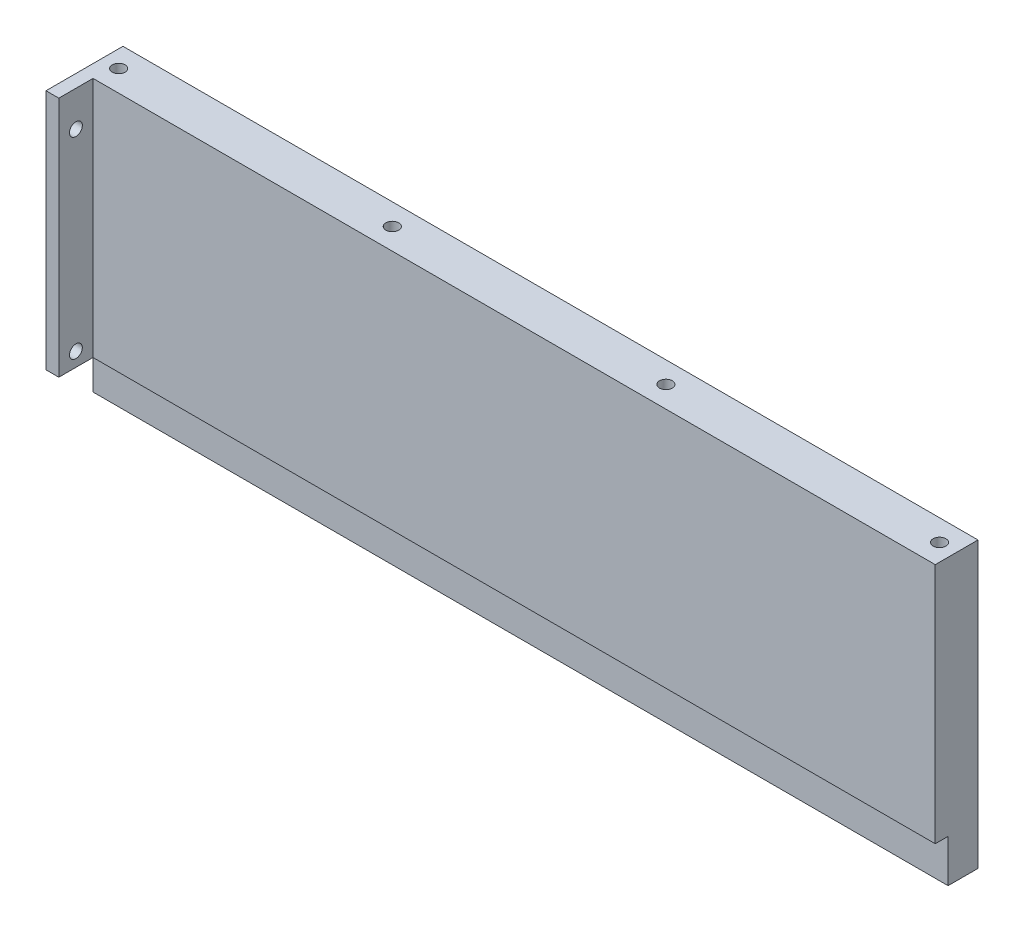
SolidWorks part; units mm, degrees
ref_plane "Front Plane" through (0, 0, 0) normal (0, 0, 1) x (1, 0, 0)
ref_plane "Top Plane" through (0, 0, 0) normal (0, 1, 0) x (1, 0, 0)
ref_plane "Right Plane" through (0, 0, 0) normal (1, 0, 0) x (0, 0, -1)
sketch "Sketch1" plane through (0, 0, 0) normal (0, 1, 0) x (1, 0, 0)
  line L1 (-100, -5) -> (100, -5)
  line L2 (-100, -5) -> (-100, 5)
  line L3 (-100, 5) -> (100, 5)
  line L4 (100, -5) -> (100, 5)
  line L5 (-100, -5) -> (100, 5) construction
  line L6 (-100, 5) -> (100, -5) construction
  point P0 (0, 0)
  point P8 (0, 0)
  dimension "D1" = 200
  dimension "D2" = 10
extrude "Boss-Extrude1" add sketch "Sketch1" along normal blind 66.54
sketch "Sketch2" plane through (0, 66.54, 0) normal (0, 1, 0) x (1, 0, 0)
  line L0 (-100, 5) -> (-100, -5) construction
  line L1 (-100, -5) -> (100, -5) construction
  circle A0 centre (-96, 0) radius 1.5
  point P4 (0, 0)
  dimension "D1" = 3
  dimension "D2" = 4
  dimension "D3" = 5
extrude "Cut-Extrude1" cut sketch "Sketch2" against normal up to next
pattern_linear "LPattern1" count 4 spacing 64 along (1, 0, 0) of "Cut-Extrude1"
sketch "Sketch3" plane through (0, 0, 5) normal (0, 0, 1) x (1, 0, 0)
  line L0 (100, 66.54) -> (100, 0) construction
  line L1 (-100, 0) -> (100, 0)
  line L2 (-100, 0) -> (-100, 10)
  line L3 (-100, 10) -> (100, 10)
  line L4 (100, 0) -> (100, 10)
  dimension "D1" = 10
extrude "Cut-Extrude2" cut sketch "Sketch3" against normal blind 3
sketch "Sketch4" plane through (0, 0, 5) normal (0, 0, 1) x (1, 0, 0)
  line L0 (100, 10) -> (-100, 10) construction
  line L1 (-100, 66.54) -> (-97, 66.54)
  line L2 (-100, 66.54) -> (-100, 10)
  line L3 (-100, 10) -> (-97, 10)
  line L4 (-97, 66.54) -> (-97, 10)
  dimension "D1" = 3
extrude "Boss-Extrude2" add sketch "Sketch4" along normal blind 8
sketch "Sketch5" plane through (-100, 0, 0) normal (-1, 0, 0) x (0, 0, 1)
  line L2 (-5, 66.54) -> (13, 66.54) construction
  line L5 (13, 66.54) -> (13, 10) construction
  circle A0 centre (9, 58.27) radius 1.5
  circle A1 centre (9, 13.27) radius 1.5
  point P4 (0, 0)
  dimension "D1" = 3
  dimension "D2" = 3
  dimension "D3" = 4
  dimension "D4" = 45
  dimension "D5" = 8.27
extrude "Cut-Extrude3" cut sketch "Sketch5" against normal up to next
